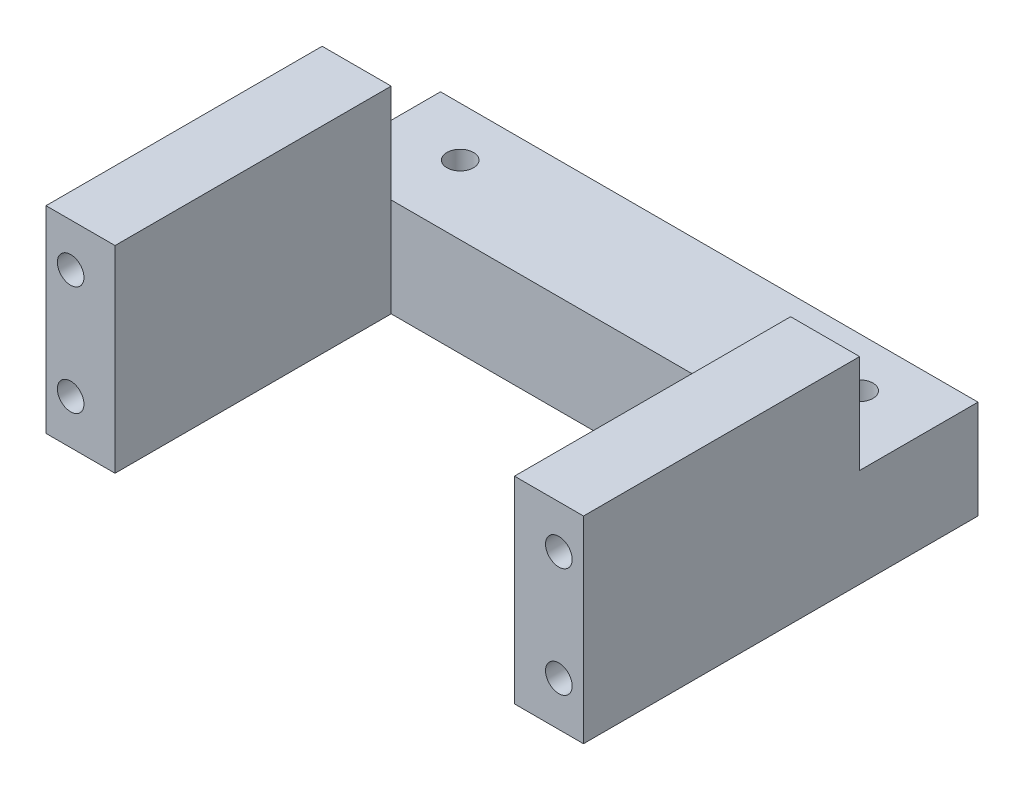
SolidWorks part; units mm, degrees
ref_plane "Alzado" through (0, 0, 0) normal (0, 0, 1) x (1, 0, 0)
ref_plane "Planta" through (0, 0, 0) normal (0, 1, 0) x (1, 0, 0)
ref_plane "Vista lateral" through (0, 0, 0) normal (1, 0, 0) x (0, 0, -1)
sketch "Croquis1" plane through (0, 0, 0) normal (0, 1, 0) x (1, 0, 0)
  line L0 (-20.25, -20) -> (-20.25, 8)
  line L1 (-27.25, -20) -> (-20.25, -20)
  line L2 (-27.25, -20) -> (-27.25, 20)
  line L3 (-27.25, 20) -> (27.25, 20)
  line L4 (27.25, -20) -> (27.25, 20)
  line L5 (-27.25, -20) -> (27.25, 20) construction
  line L6 (-27.25, 20) -> (27.25, -20) construction
  line L7 (-20.25, 8) -> (20.25, 8)
  line L8 (20.25, 8) -> (20.25, -20)
  line L9 (0, 18.1511) -> (0, 11.6364) construction
  line L10 (20.25, -20) -> (27.25, -20)
  circle A0 centre (-20.25, 15) radius 1.35
  circle A1 centre (20.25, 15) radius 1.35
  point P0 (0, 0)
  dimension "D6" = 2.7
  dimension "D7" = 5
  dimension "D1" = 54.5
  dimension "D2" = 40
  dimension "D3" = 7
  dimension "D4" = 7
  dimension "D5" = 28
extrude "Saliente-Extruir1" add sketch "Croquis1" along normal blind 10
sketch "Croquis2" plane through (0, 0, 0) normal (0, 1, 0) x (1, 0, 0)
  line L0 (-20.25, -20) -> (-20.25, 8)
  line L1 (-27.25, -20) -> (-20.25, -20)
  line L2 (-27.25, -20) -> (-27.25, 8)
  line L4 (27.25, -20) -> (27.25, 8)
  line L5 (-27.25, -20) -> (-20.25, -14.8624) construction
  line L6 (20.25, 8) -> (27.25, 8)
  line L8 (20.25, 8) -> (20.25, -20)
  line L9 (20.25, -14.8624) -> (27.25, -20) construction
  line L10 (20.25, -20) -> (27.25, -20)
  line L11 (-27.25, 8) -> (-20.25, 8)
  point P0 (0, 0)
  dimension "D3" = 7
  dimension "D4" = 7
extrude "Saliente-Extruir2" add sketch "Croquis2" along normal blind 20
sketch "Croquis3" plane through (0, 0, 20) normal (0, 0, 1) x (1, 0, 0)
  line L0 (-27.25, 20) -> (-20.25, 20) construction
  line L1 (-20.25, 20) -> (-20.25, 0) construction
  line L2 (-27.25, 0) -> (-20.25, 0) construction
  line L3 (-20.25, 10) -> (-20.25, 0) construction
  circle A0 centre (-24.75, 15.6125) radius 1.35
  circle A1 centre (-24.75, 4.5) radius 1.35
  circle A2 centre (24.75, 4.5) radius 1.35
  circle A3 centre (24.75, 15.6125) radius 1.35
  point P4 (-23.75, 20)
  point P11 (-23.75, 0)
  dimension "D1" = 2.7
  dimension "D2" = 4.5
  dimension "D3" = 4.5
  dimension "D4" = 2.7
  dimension "D5" = 4.5
  dimension "D6" = 4.5
extrude "Cortar-Extruir1" cut sketch "Croquis3" against normal blind 15
